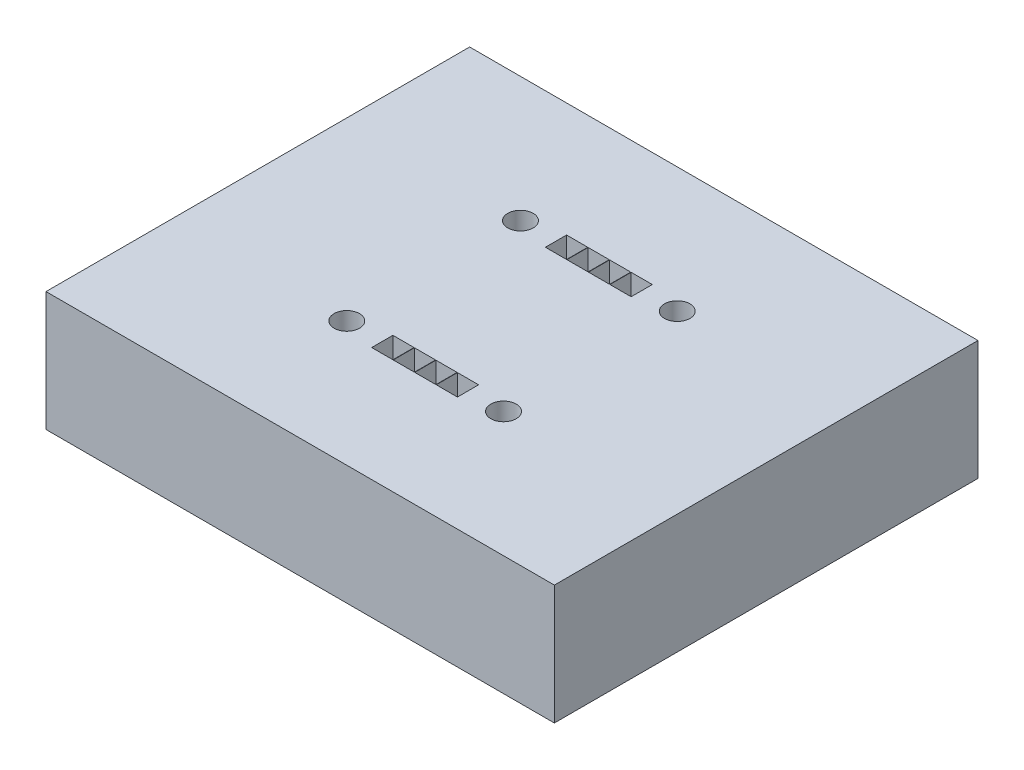
SolidWorks part; units mm, degrees
ref_plane "Plan de face" through (0, 0, 0) normal (0, 0, 1) x (1, 0, 0)
ref_plane "Plan de dessus" through (0, 0, 0) normal (0, 1, 0) x (1, 0, 0)
ref_plane "Plan de droite" through (0, 0, 0) normal (1, 0, 0) x (0, 0, -1)
sketch "Esquisse1" plane through (0, 0, 0) normal (0, 1, 0) x (1, 0, 0)
  line L1 (30, 25) -> (-30, 25)
  line L2 (30, 25) -> (30, -25)
  line L3 (30, -25) -> (-30, -25)
  line L4 (-30, 25) -> (-30, -25)
  line L5 (30, 25) -> (-30, -25) construction
  line L6 (30, -25) -> (-30, 25) construction
  point P0 (0, 0)
  dimension "D1" = 50
  dimension "D2" = 60
extrude "Boss.-Extru.2" add sketch "Esquisse1" along normal blind 14.1 contours L4 L3 L2 L1
sketch "Esquisse2" plane through (0, 14.1, 0) normal (0, 1, 0) x (1, 0, 0)
  line L0 (-9.25, 0) -> (9.25, 0) construction
  line L2 (-9.25, 10.25) -> (9.25, 10.25) construction
  line L8 (2.56, -9) -> (5.06, -9)
  line L9 (-5.06, 11.5) -> (-2.56, 11.5)
  line L72 (-5.06, 11.5) -> (-5.06, 9)
  line L73 (5.06, -11.5) -> (5.06, -9)
  line L74 (2.56, -11.5) -> (5.06, -11.5)
  line L75 (-5.06, 9) -> (-2.56, 9)
  line L76 (2.56, -11.5) -> (2.56, -9)
  line L77 (0.02, -9) -> (2.52, -9)
  line L78 (-2.56, 11.5) -> (-2.56, 9)
  line L79 (-5.06, 11.5) -> (-2.56, 9) construction
  line L80 (-5.06, 9) -> (-2.56, 11.5) construction
  line L81 (-2.52, 11.5) -> (-0.02, 11.5)
  line L82 (-2.52, 11.5) -> (-2.52, 9)
  line L83 (-2.52, 9) -> (-0.02, 9)
  line L84 (-0.02, 11.5) -> (-0.02, 9)
  line L85 (-2.52, 11.5) -> (-0.02, 9) construction
  line L86 (-2.52, 9) -> (-0.02, 11.5) construction
  line L87 (0.02, 11.5) -> (2.52, 11.5)
  line L88 (0.02, 11.5) -> (0.02, 9)
  line L89 (0.02, 9) -> (2.52, 9)
  line L90 (2.52, 11.5) -> (2.52, 9)
  line L91 (0.02, 11.5) -> (2.52, 9) construction
  line L92 (0.02, 9) -> (2.52, 11.5) construction
  line L93 (2.56, 11.5) -> (5.06, 11.5)
  line L94 (2.56, 11.5) -> (2.56, 9)
  line L95 (2.56, 9) -> (5.06, 9)
  line L96 (5.06, 11.5) -> (5.06, 9)
  line L97 (2.56, 11.5) -> (5.06, 9) construction
  line L98 (2.56, 9) -> (5.06, 11.5) construction
  line L99 (2.52, -11.5) -> (2.52, -9)
  line L100 (0.02, -11.5) -> (2.52, -11.5)
  line L101 (0.02, -11.5) -> (0.02, -9)
  line L102 (-2.52, -9) -> (-0.02, -9)
  line L103 (-0.02, -11.5) -> (-0.02, -9)
  line L104 (-2.52, -11.5) -> (-0.02, -11.5)
  line L105 (-2.52, -11.5) -> (-2.52, -9)
  line L106 (-5.06, -9) -> (-2.56, -9)
  line L107 (-2.56, -11.5) -> (-2.56, -9)
  line L108 (-5.06, -11.5) -> (-2.56, -11.5)
  line L109 (-5.06, -11.5) -> (-5.06, -9)
  circle A5 centre (-9.25, 10.25) radius 1.5
  circle A6 centre (9.25, 10.25) radius 1.5
  circle A11 centre (9.25, -10.25) radius 1.5
  circle A16 centre (-9.25, -10.25) radius 1.5
  dimension "D8" = 2.5
  dimension "D2" = 3
  dimension "D1" = 18.5
  dimension "D9" = 10.25
extrude "Enlèv. mat.-Extru.1" cut sketch "Esquisse2" against normal through all
